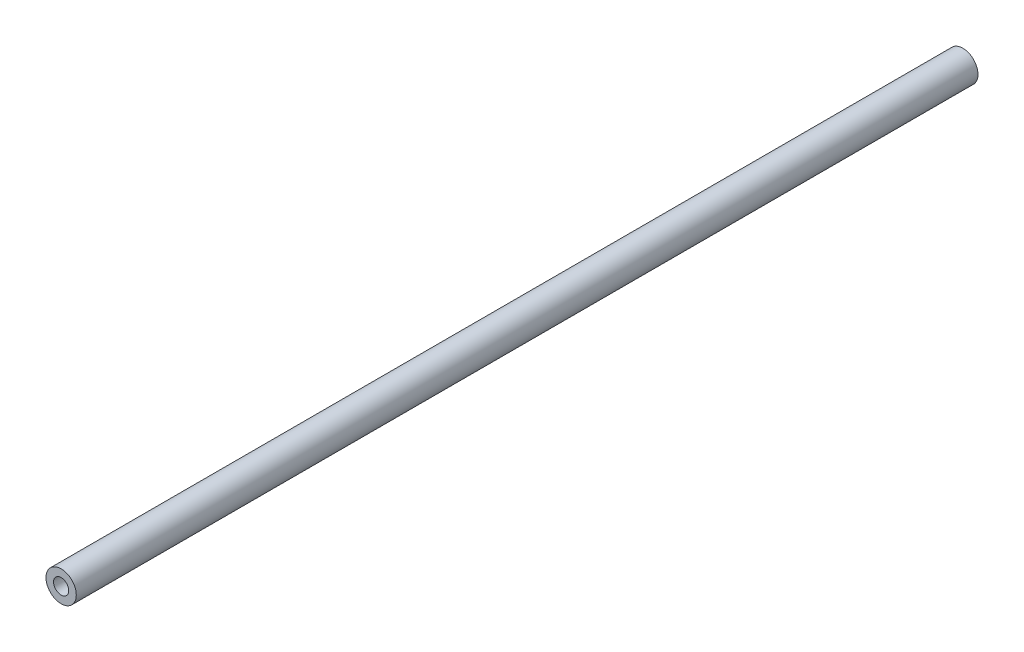
SolidWorks part; units mm, degrees
material "VITON"
ref_plane "Front" through (0, 0, 0) normal (0, 0, 1) x (1, 0, 0)
ref_plane "Top" through (0, 0, 0) normal (0, 1, 0) x (1, 0, 0)
ref_plane "Right" through (0, 0, 0) normal (1, 0, 0) x (0, 0, -1)
sketch "Sketch1" plane through (0, 0, 0) normal (0, 0, 1) x (1, 0, 0)
  circle A0 centre (0, 0) radius 2
extrude "Boss-Extrude1" add sketch "Sketch1" along normal blind 119
sketch "Sketch2" plane through (0, 0, 0) normal (0, 0, -1) x (-1, 0, 0)
  circle A0 centre (0, 0) radius 1
extrude "Cut-Extrude1" cut sketch "Sketch2" against normal blind 119
